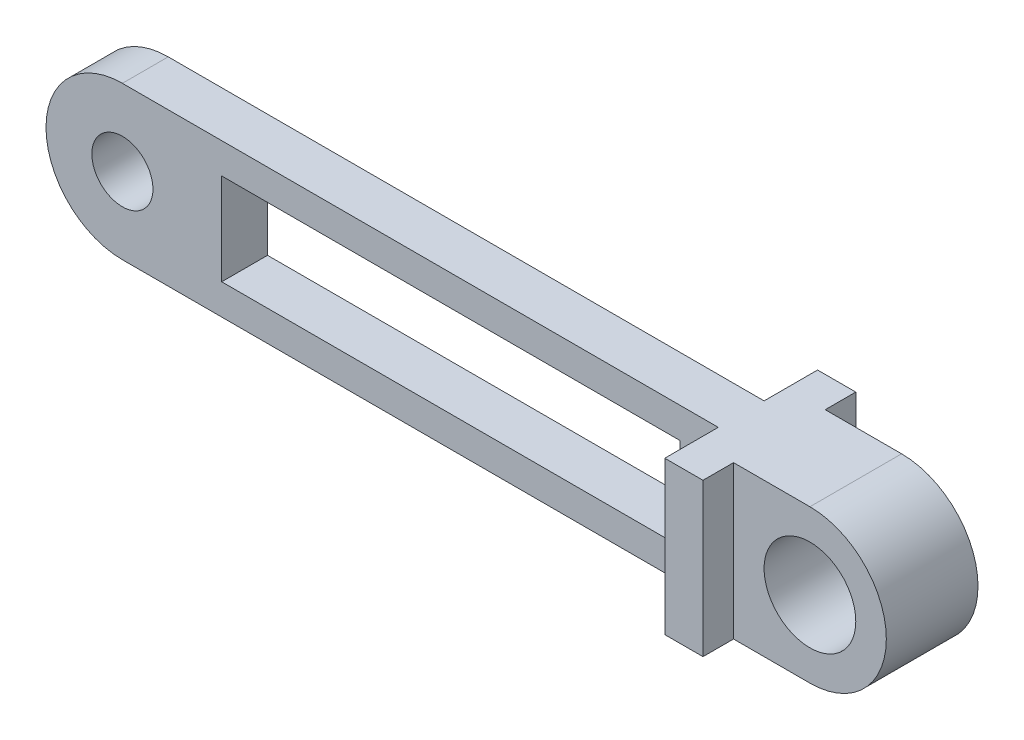
SolidWorks part; units mm, degrees
ref_plane "前视基准面" through (0, 0, 0) normal (0, 0, 1) x (1, 0, 0)
ref_plane "上视基准面" through (0, 0, 0) normal (0, 1, 0) x (1, 0, 0)
ref_plane "右视基准面" through (0, 0, 0) normal (1, 0, 0) x (0, 0, -1)
sketch "草图1" plane through (0, 0, 0) normal (0, 0, 1) x (1, 0, 0)
  line L0 (0, -10) -> (0, 10) construction
  line L1 (-35, 10) -> (35, 10)
  line L2 (-30, 6) -> (30, 6)
  line L3 (-35, -10) -> (35, -10)
  line L4 (35, 10) -> (35, -10)
  line L5 (-30, 6) -> (-30, -6)
  line L6 (-30, -6) -> (30, -6)
  line L7 (-43, 10) -> (-35, 10)
  line L8 (-43, -10) -> (-35, -10)
  line L9 (30, 6) -> (30, -6)
  line L10 (-30, 6) -> (30, -6) construction
  line L11 (-30, -6) -> (30, 6) construction
  circle A0 centre (-43, 0) radius 4
  arc A1 (-43, 10) -> (-43, -10) centre (-43, 0) ccw
  point P0 (0, 0)
  point P6 (0, 0)
  dimension "D3" = 8
  dimension "D7" = 5
  dimension "D1" = 70
  dimension "D2" = 20
  dimension "D4" = 8
  dimension "D5" = 10
  dimension "D6" = 35
  dimension "D8" = 4
extrude "凸台-拉伸1" add sketch "草图1" along normal mid plane 6
sketch "草图2" plane through (0, 0, 0) normal (1, 0, 0) x (0, 0, -1)
  line L1 (-10, 10) -> (10, 10)
  line L2 (-10, 10) -> (-10, -10)
  line L3 (-10, -10) -> (10, -10)
  line L4 (10, 10) -> (10, -10)
  line L5 (-10, 10) -> (10, -10) construction
  line L6 (-10, -10) -> (10, 10) construction
  point P0 (0, 0)
  dimension "D1" = 20
  dimension "D2" = 20
extrude "凸台-拉伸2" add sketch "草图2" along normal blind 5 from offset 35
sketch "草图3" plane through (0, 0, 0) normal (0, 0, 1) x (1, 0, 0)
  line L0 (40, 10) -> (50, 10)
  line L1 (50, -10) -> (40, -10)
  line L2 (40, -10) -> (40, 10)
  arc A0 (50, 10) -> (50, -10) centre (50, 0) cw
  circle A1 centre (50, 0) radius 6
  dimension "D1" = 12
  dimension "D2" = 10
extrude "凸台-拉伸3" add sketch "草图3" along normal mid plane 12
